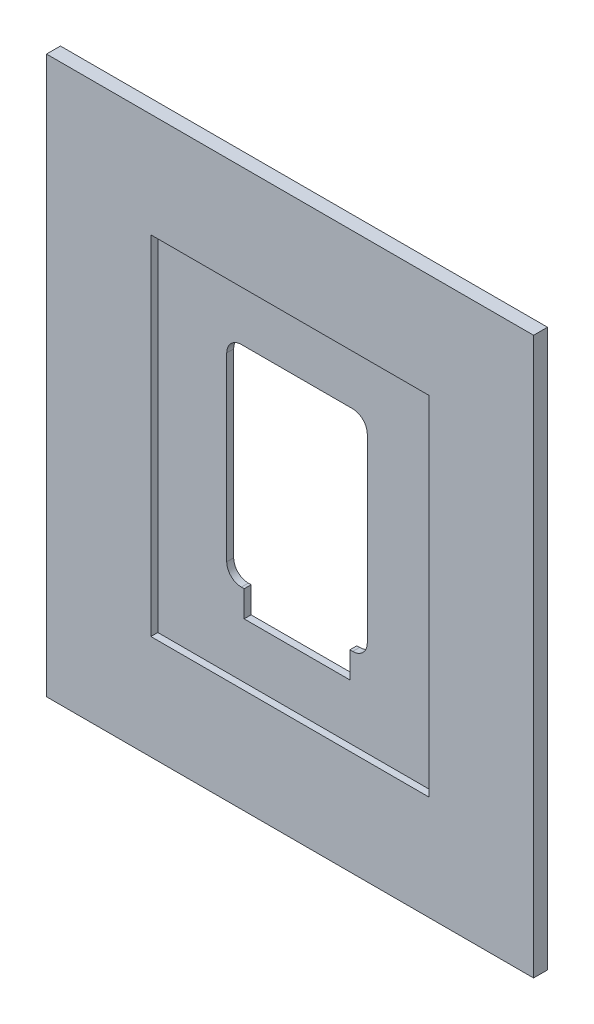
SolidWorks part; units mm, degrees
ref_plane "前视基准面" through (0, 0, 0) normal (0, 0, 1) x (1, 0, 0)
ref_plane "上视基准面" through (0, 0, 0) normal (0, 1, 0) x (1, 0, 0)
ref_plane "右视基准面" through (0, 0, 0) normal (1, 0, 0) x (0, 0, -1)
sketch "草图1" plane through (0, 0, 0) normal (0, 0, 1) x (1, 0, 0)
  line L1 (-70, 80) -> (70, 80)
  line L2 (-70, 80) -> (-70, -80)
  line L3 (-70, -80) -> (70, -80)
  line L4 (70, 80) -> (70, -80)
  line L5 (-70, 80) -> (70, -80) construction
  line L6 (-70, -80) -> (70, 80) construction
  point P0 (0, 0)
  dimension "D1" = 160
  dimension "D2" = 140
extrude "凸台-拉伸1" add sketch "草图1" along normal blind 2
sketch "草图2" plane through (0, 0, 2) normal (0, 0, 1) x (1, 0, 0)
  line L1 (-40, 50) -> (40, 50)
  line L2 (-40, 50) -> (-40, -50)
  line L3 (-40, -50) -> (40, -50)
  line L4 (70, -80) -> (70, 80)
  line L5 (70, 80) -> (-70, 80)
  line L6 (-70, 80) -> (-70, -80)
  line L7 (-70, -80) -> (70, -80)
  line L8 (70, -80) -> (70, 80)
  line L9 (70, 80) -> (-70, 80)
  line L10 (-70, 80) -> (-70, -80)
  line L11 (-70, -80) -> (70, -80)
  line L12 (40, 50) -> (40, -50)
  line L13 (-40, 50) -> (40, -50) construction
  line L14 (-40, -50) -> (40, 50) construction
  point P2 (0, 0)
  dimension "D2" = 100
  dimension "D3" = 80
  dimension "D1" = 0
extrude "凸台-拉伸2" add sketch "草图2" along normal blind 2
sketch "草图4" plane through (0, 0, 2) normal (0, 0, 1) x (1, 0, 0)
  line L0 (0, 3.5) -> (0, -50) construction
  line L1 (-6.8, -34.2) -> (-11.2, -34.2)
  line L9 (6.8, -34.2) -> (-6.8, -34.2)
  line L12 (15.2, -34.2) -> (10.8, -34.2)
  line L15 (15.2, -26.7) -> (15.2, -34.2)
  line L19 (16, -26.7) -> (15.2, -26.7)
  line L21 (20.2, 29.5) -> (20.2, -22.5)
  line L24 (-20.2, -22.5) -> (-20.2, 29.5)
  line L28 (-15.2, -26.7) -> (-16, -26.7)
  line L29 (15.2, -26.7) -> (16, -26.7)
  line L31 (20.2, -22.5) -> (20.2, 29.5)
  line L32 (16, 33.7) -> (-16, 33.7)
  line L35 (-20.2, 29.5) -> (-20.2, -22.5)
  line L42 (-16, -26.7) -> (-15.2, -26.7)
  line L43 (-15.2, -26.7) -> (-15.2, -34.2)
  line L44 (-15.2, -34.2) -> (-10.8, -34.2)
  line L45 (-6.8, -34.2) -> (6.8, -34.2)
  line L47 (6.8, -34.2) -> (11.2, -34.2)
  arc A32 (20.2, -22.5) -> (16, -26.7) centre (16, -22.5) cw
  arc A33 (16, 33.7) -> (20.2, 29.5) centre (16, 29.5) cw
  arc A34 (-20.2, 29.5) -> (-16, 33.7) centre (-16, 29.5) cw
  arc A35 (-16, -26.7) -> (-20.2, -22.5) centre (-16, -22.5) cw
  arc A36 (16, -26.7) -> (20.2, -22.5) centre (16, -22.5) ccw
  arc A37 (20.2, 29.5) -> (16, 33.7) centre (16, 29.5) ccw
  arc A38 (-16, 33.7) -> (-20.2, 29.5) centre (-16, 29.5) ccw
  arc A39 (-20.2, -22.5) -> (-16, -26.7) centre (-16, -22.5) ccw
extrude "切除-拉伸1" cut sketch "草图4" against normal blind 2
